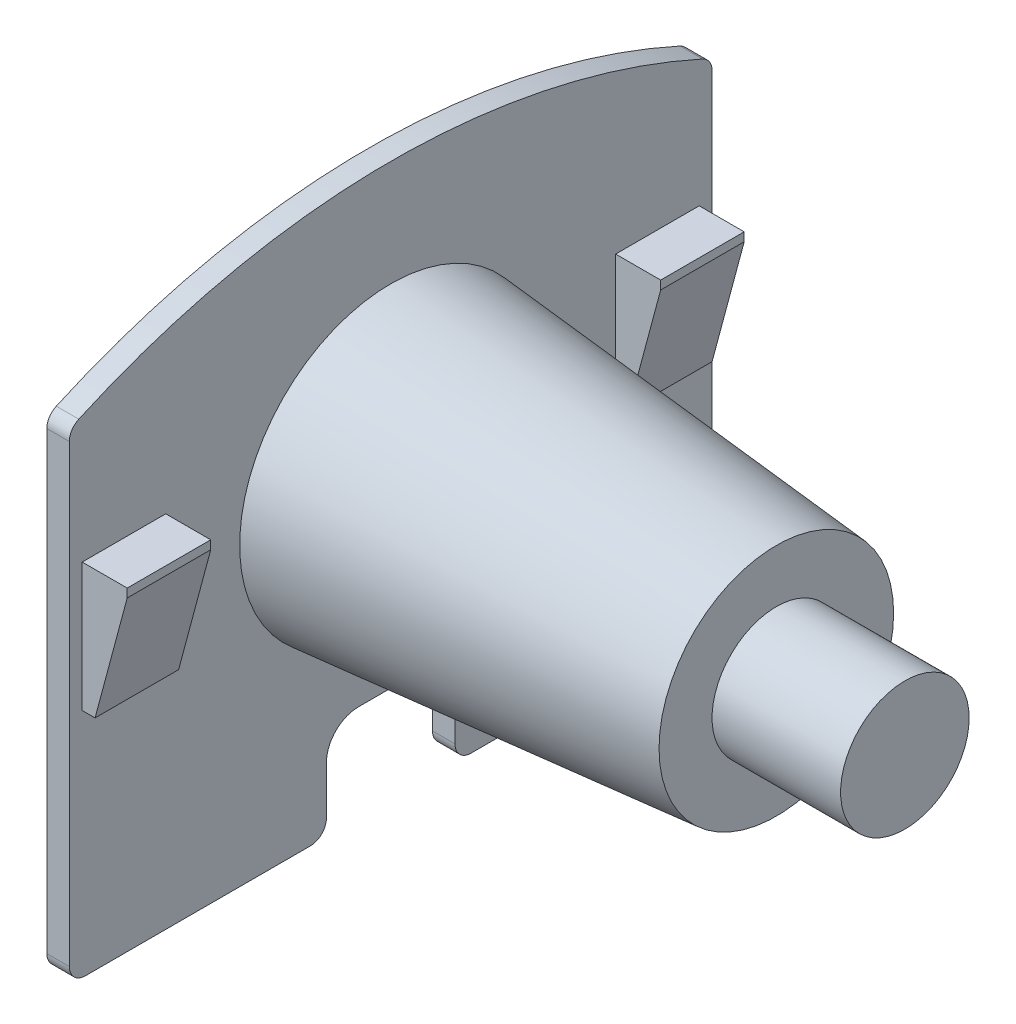
SolidWorks part; units mm, degrees
ref_plane "Front Plane" through (0, 0, 0) normal (0, 0, 1) x (1, 0, 0)
ref_plane "Top Plane" through (0, 0, 0) normal (0, 1, 0) x (1, 0, 0)
ref_plane "Right Plane" through (0, 0, 0) normal (1, 0, 0) x (0, 0, -1)
sketch "Sketch1" plane through (0, 0, 0) normal (1, 0, 0) x (0, 0, -1)
  circle A0 centre (0, 0) radius 2.35
  dimension "D1" = 4.7
extrude "Boss-Extrude1" add sketch "Sketch1" along normal blind 6 draft 5
sketch "Sketch2" plane through (0, 0, 0) normal (1, 0, 0) x (0, 0, -1)
  line L0 (1, -4.6) -> (5, -4.6)
  line L1 (-5, -4.6) -> (-1, -4.6)
  line L2 (-5, -4.6) -> (-5, 2.4954)
  line L3 (-5, 2.4954) -> (5, 2.4954) construction
  line L4 (5, -4.6) -> (5, 2.4954)
  line L5 (-5, -4.6) -> (5, 2.4954) construction
  line L6 (-5, 2.4954) -> (5, -4.6) construction
  line L7 (-5, 2.4954) -> (5, 2.4954) construction
  line L8 (-5, 2.4954) -> (-5, 2.8843)
  line L9 (-5, 4) -> (5, 4) construction
  line L10 (5, 2.4954) -> (5, 2.8843)
  line L11 (-1.8251, 0) -> (-2.5, 0) construction
  line L12 (-1, -4.6) -> (-1, -3.1)
  line L13 (-1, -3.1) -> (1, -3.1)
  line L14 (1, -4.6) -> (1, -3.1)
  line L15 (1.8251, 0) -> (-1.8251, 0) construction
  circle A0 centre (0, 0) radius 1.8251 construction
  arc A1 (5, 2.8843) -> (-5, 2.8843) centre (0, -7.762) ccw
  point P0 (0, 0.5296)
  dimension "D1" = 10
  dimension "D2" = 8.6
  dimension "D3" = 4
  dimension "D4" = 4
  dimension "D5" = 1.5
  dimension "D6" = 4
extrude "Boss-Extrude2" add sketch "Sketch2" against normal blind 0.35
sketch "Sketch3" plane through (0, 0, 0) normal (1, 0, 0) x (0, 0, -1)
  line L0 (-5, 2.8843) -> (-5, -4.6) construction
  line L1 (-4.8, 1) -> (-3.5, 1)
  line L2 (-4.8, 1) -> (-4.8, -1)
  line L3 (-4.8, -1) -> (-3.5, -1)
  line L4 (-3.5, 1) -> (-3.5, -1)
  line L5 (-5, -4.6) -> (-1, -4.6) construction
  line L6 (0, 0) -> (0, 4.4839) construction
  line L7 (3.5, 1) -> (3.5, -1)
  line L8 (4.8, -1) -> (3.5, -1)
  line L9 (4.8, 1) -> (4.8, -1)
  line L10 (4.8, 1) -> (3.5, 1)
  dimension "D1" = 0.2
  dimension "D2" = 1.3
  dimension "D3" = 3.6
  dimension "D4" = 5.6
extrude "Boss-Extrude3" add sketch "Sketch3" along normal blind 0.7
chamfer "Chamfer1" distance 0.5 angle 75 2 edges at (0.7, -1, -4.15) (0.7, -1, 4.15)
fillet "Fillet2" radius 0.5 2 edges at (-0.175, -3.1, -1) (-0.175, -3.1, 1)
fillet "Fillet3" radius 0.25 6 edges at (-0.175, -4.6, 5) (-0.175, -4.6, 1) (-0.175, -4.6, -1) (-0.175, -4.6, -5) (-0.175, 2.8843, -5) (-0.175, 2.8843, 5)
sketch "Sketch4" plane through (0, 0, 0) normal (1, 0, 0) x (0, 0, -1)
  circle A0 centre (0, 0) radius 1
extrude "Boss-Extrude4" add sketch "Sketch4" along normal blind 8
